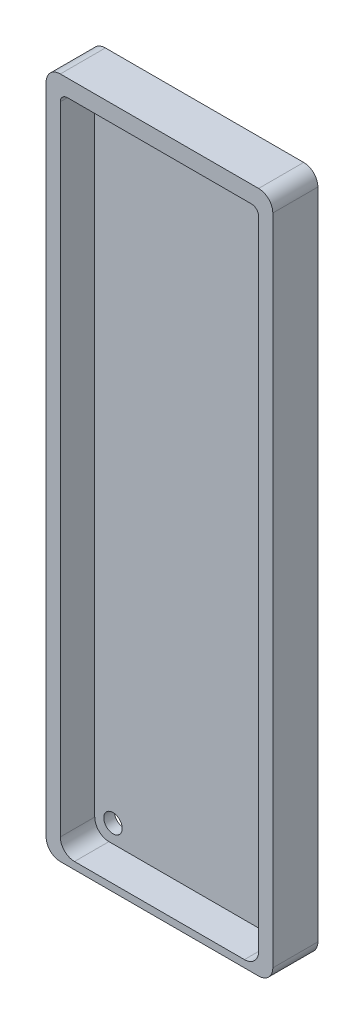
SolidWorks part; units mm, degrees
material "Plastique personnalisé"
ref_plane "Plan de face" through (0, 0, 0) normal (0, 0, 1) x (1, 0, 0)
ref_plane "Plan de dessus" through (0, 0, 0) normal (0, 1, 0) x (1, 0, 0)
ref_plane "Plan de droite" through (0, 0, 0) normal (1, 0, 0) x (0, 0, -1)
sketch "Model" plane through (0, 0, 0) normal (0, 0, 1) x (1, 0, 0)
  line L1773 (110.49, -34.8139) -> (110.49, -38.6239)
  line L1774 (83.82, -33.5439) -> (109.22, -33.5439)
  line L1775 (82.55, -38.6239) -> (82.55, -34.8139)
  line L1776 (82.55, -39.8939) -> (82.55, -123.7139)
  line L1777 (110.49, -39.8939) -> (110.49, -123.7139)
  line L1778 (82.55, -39.8939) -> (82.55, -38.6239)
  line L1779 (110.49, -39.8939) -> (110.49, -38.6239)
  line L1780 (85.09, -126.2539) -> (107.95, -126.2539)
  spline S0 degree 3 poles (109.22, -36.0839) (109.22, -36.5377) (108.9779, -36.9569) (108.585, -37.1838) knots 0 0 0 0 1 1 1 1
  spline S1 degree 3 poles (108.585, -37.1838) (108.1921, -37.4106) (107.7079, -37.4106) (107.315, -37.1838) knots 0 0 0 0 1 1 1 1
  spline S2 degree 3 poles (107.315, -37.1838) (106.9221, -36.9569) (106.68, -36.5377) (106.68, -36.0839) knots 0 0 0 0 1 1 1 1
  spline S3 degree 3 poles (106.68, -36.0839) (106.68, -35.6302) (106.9221, -35.2109) (107.315, -34.9841) knots 0 0 0 0 1 1 1 1
  spline S4 degree 3 poles (107.315, -34.9841) (107.7079, -34.7572) (108.1921, -34.7572) (108.585, -34.9841) knots 0 0 0 0 1 1 1 1
  spline S5 degree 3 poles (108.585, -34.9841) (108.9779, -35.2109) (109.22, -35.6302) (109.22, -36.0839) knots 0 0 0 0 1 1 1 1
  spline S6 degree 3 poles (86.36, -36.0839) (86.36, -36.5377) (86.1179, -36.9569) (85.725, -37.1838) knots 0 0 0 0 1 1 1 1
  spline S7 degree 3 poles (85.725, -37.1838) (85.3321, -37.4106) (84.8479, -37.4106) (84.455, -37.1838) knots 0 0 0 0 1 1 1 1
  spline S8 degree 3 poles (84.455, -37.1838) (84.0621, -36.9569) (83.82, -36.5377) (83.82, -36.0839) knots 0 0 0 0 1 1 1 1
  spline S9 degree 3 poles (83.82, -36.0839) (83.82, -35.6302) (84.0621, -35.2109) (84.455, -34.9841) knots 0 0 0 0 1 1 1 1
  spline S10 degree 3 poles (84.455, -34.9841) (84.8479, -34.7572) (85.3321, -34.7572) (85.725, -34.9841) knots 0 0 0 0 1 1 1 1
  spline S11 degree 3 poles (85.725, -34.9841) (86.1179, -35.2109) (86.36, -35.6302) (86.36, -36.0839) knots 0 0 0 0 1 1 1 1
  spline S12 degree 3 poles (110.49, -34.8139) (110.49, -34.4771) (110.3562, -34.1541) (110.118, -33.9159) knots 0 0 0 0 1 1 1 1
  spline S13 degree 3 poles (110.118, -33.9159) (109.8799, -33.6777) (109.5568, -33.5439) (109.22, -33.5439) knots 0 0 0 0 1 1 1 1
  spline S14 degree 3 poles (83.82, -33.5439) (83.4832, -33.5439) (83.1601, -33.6777) (82.922, -33.9159) knots 0 0 0 0 1 1 1 1
  spline S15 degree 3 poles (82.922, -33.9159) (82.6838, -34.1541) (82.55, -34.4771) (82.55, -34.8139) knots 0 0 0 0 1 1 1 1
  spline S16 degree 3 poles (82.55, -123.7139) (82.55, -124.3876) (82.8176, -125.0336) (83.2939, -125.51) knots 0 0 0 0 1 1 1 1
  spline S17 degree 3 poles (83.2939, -125.51) (83.7703, -125.9863) (84.4163, -126.2539) (85.09, -126.2539) knots 0 0 0 0 1 1 1 1
  spline S18 degree 3 poles (107.95, -126.2539) (108.6236, -126.2539) (109.2697, -125.9863) (109.7461, -125.51) knots 0 0 0 0 1 1 1 1
  spline S19 degree 3 poles (109.7461, -125.51) (110.2224, -125.0336) (110.49, -124.3876) (110.49, -123.7139) knots 0 0 0 0 1 1 1 1
  spline S20 degree 3 poles (86.36, -123.7139) (86.36, -124.1677) (86.1179, -124.5869) (85.725, -124.8138) knots 0 0 0 0 1 1 1 1
  spline S21 degree 3 poles (85.725, -124.8138) (85.3321, -125.0406) (84.8479, -125.0406) (84.455, -124.8138) knots 0 0 0 0 1 1 1 1
  spline S22 degree 3 poles (84.455, -124.8138) (84.0621, -124.5869) (83.82, -124.1677) (83.82, -123.7139) knots 0 0 0 0 1 1 1 1
  spline S23 degree 3 poles (83.82, -123.7139) (83.82, -123.2602) (84.0621, -122.8409) (84.455, -122.6141) knots 0 0 0 0 1 1 1 1
  spline S24 degree 3 poles (84.455, -122.6141) (84.8479, -122.3872) (85.3321, -122.3872) (85.725, -122.6141) knots 0 0 0 0 1 1 1 1
  spline S25 degree 3 poles (85.725, -122.6141) (86.1179, -122.8409) (86.36, -123.2602) (86.36, -123.7139) knots 0 0 0 0 1 1 1 1
  spline S26 degree 3 poles (109.22, -123.7139) (109.22, -124.1677) (108.9779, -124.5869) (108.585, -124.8138) knots 0 0 0 0 1 1 1 1
  spline S27 degree 3 poles (108.585, -124.8138) (108.1921, -125.0406) (107.7079, -125.0406) (107.315, -124.8138) knots 0 0 0 0 1 1 1 1
  spline S28 degree 3 poles (107.315, -124.8138) (106.9221, -124.5869) (106.68, -124.1677) (106.68, -123.7139) knots 0 0 0 0 1 1 1 1
  spline S29 degree 3 poles (106.68, -123.7139) (106.68, -123.2602) (106.9221, -122.8409) (107.315, -122.6141) knots 0 0 0 0 1 1 1 1
  spline S30 degree 3 poles (107.315, -122.6141) (107.7079, -122.3872) (108.1921, -122.3872) (108.585, -122.6141) knots 0 0 0 0 1 1 1 1
  spline S31 degree 3 poles (108.585, -122.6141) (108.9779, -122.8409) (109.22, -123.2602) (109.22, -123.7139) knots 0 0 0 0 1 1 1 1
extrude "Boss.-Extru.1" add sketch "Model" along normal blind 1.5
sketch "Esquisse1" plane through (0, 0, 0) normal (0, 0, -1) x (-1, 0, 0)
  line L0 (-96.52, -33.5439) -> (-115.865, -33.5439) construction
  line L1 (-109.22, -33.5439) -> (-83.82, -33.5439) construction
  line L2 (-110.49, -43.7978) -> (-110.49, -28.2724) construction
  line L3 (-110.49, -123.7139) -> (-110.49, -34.8139) construction
  line L4 (-96.52, -33.5439) -> (-77.5062, -33.5439) construction
  line L5 (-82.55, -44.1721) -> (-82.55, -28.5755) construction
  line L6 (-82.55, -34.8139) -> (-82.55, -123.7139) construction
  line L7 (-96.52, -126.2539) -> (-118.6079, -126.2539) construction
  line L8 (-85.09, -126.2539) -> (-107.95, -126.2539) construction
  line L9 (-118.6079, -126.2539) -> (-70.8635, -126.2539) construction
  line L10 (-110.49, -109.9168) -> (-110.49, -132.8125) construction
  line L11 (-82.55, -108.7873) -> (-82.55, -133.2125) construction
  line L12 (-87.9303, -127.2639) -> (-124.6351, -127.2639) construction
  line L13 (-109.49, -33.5439) -> (-83.55, -33.5439)
  line L14 (-110.49, -34.5439) -> (-110.49, -124.2539)
  line L15 (-108.49, -126.2539) -> (-84.55, -126.2539)
  line L16 (-82.55, -34.5439) -> (-82.55, -124.2539)
  line L17 (-110.49, -127.2639) -> (-82.55, -127.2639) construction
  line L18 (-124.6351, -127.2639) -> (-68.2696, -127.2639) construction
  line L19 (-112.2458, -115.6849) -> (-112.49, -134.0257) construction
  line L20 (-80.55, -113.8817) -> (-80.55, -139.2) construction
  line L21 (-80.55, -125.2639) -> (-80.55, -33.1529) construction
  line L22 (-112.49, -49.0821) -> (-112.49, -27.4348) construction
  line L23 (-112.49, -33.1529) -> (-112.49, -125.2639) construction
  line L24 (-92.2697, -31.1529) -> (-118.4336, -31.1529) construction
  line L25 (-82.55, -31.1529) -> (-110.49, -31.1529) construction
  line L26 (-110.49, -31.1529) -> (-82.55, -31.1529)
  line L28 (-112.49, -33.1529) -> (-112.49, -125.2639)
  line L29 (-110.49, -127.2639) -> (-82.55, -127.2639)
  line L30 (-80.55, -33.1529) -> (-80.55, -125.2639)
  arc A0 (-83.55, -33.5439) -> (-82.55, -34.5439) centre (-83.55, -34.5439) cw
  arc A1 (-109.49, -33.5439) -> (-110.49, -34.5439) centre (-109.49, -34.5439) ccw
  arc A2 (-84.55, -126.2539) -> (-82.55, -124.2539) centre (-84.55, -124.2539) ccw
  arc A3 (-110.49, -124.2539) -> (-108.49, -126.2539) centre (-108.49, -124.2539) ccw
  arc A6 (-82.55, -127.2639) -> (-80.55, -125.2639) centre (-82.55, -125.2639) ccw
  arc A7 (-112.49, -125.2639) -> (-110.49, -127.2639) centre (-110.49, -125.2639) ccw
  arc A8 (-112.49, -33.1529) -> (-110.49, -31.1529) centre (-110.49, -33.1529) cw
  arc A9 (-80.55, -33.1529) -> (-82.55, -31.1529) centre (-82.55, -33.1529) ccw
  point P30 (-110.49, -33.5439)
  point P33 (-82.55, -126.2539)
  point P63 (-112.49, -31.1529)
  point P66 (-80.55, -127.2639)
  dimension "D1" = 1
  dimension "D2" = 2
  dimension "D3" = 2
  dimension "D4" = 2
  dimension "D5" = 2
extrude "Boss.-Extru.2" add sketch "Esquisse1" against normal up to surface (6.35 mm away)
sketch "Esquisse2" plane through (0, 0, 1.5) normal (0, 0, 1) x (1, 0, 0)
  line L0 (82.8629, -122.8035) -> (81.7189, -124.05)
  line L1 (81.8173, -35.4386) -> (83.866, -35.4386)
  line L2 (81.8173, -35.4386) -> (81.8173, -32.7164)
  line L3 (81.8173, -32.7164) -> (83.866, -32.7164)
  line L4 (83.866, -35.4386) -> (83.866, -32.7164)
  line L5 (108.6397, -32.792) -> (111.0237, -32.792)
  line L6 (108.6397, -32.792) -> (108.6397, -34.7862)
  line L7 (108.6397, -34.7862) -> (111.0237, -34.7862)
  line L8 (111.0237, -32.792) -> (111.0237, -34.7862)
  line L9 (81.7189, -124.05) -> (82.8629, -126.4489)
  line L10 (82.8629, -126.4489) -> (85.4924, -126.7819)
  line L11 (85.4924, -126.7819) -> (85.4412, -125.8172)
  line L12 (85.4412, -125.8172) -> (83.7935, -125.0232)
  line L13 (83.7935, -125.0232) -> (83.0593, -123.828)
  line L14 (83.0593, -123.828) -> (82.8629, -122.8035)
  line L15 (111.0798, -122.6986) -> (110.0172, -123.5038)
  line L16 (110.0172, -123.5038) -> (109.2019, -125.1958)
  line L17 (109.2019, -125.1958) -> (107.3198, -125.5565)
  line L18 (107.3198, -125.5565) -> (107.1787, -126.6708)
  line L19 (107.1787, -126.6708) -> (110.2746, -126.6154)
  line L20 (110.2746, -126.6154) -> (111.5063, -125.4688)
  line L21 (111.5063, -125.4688) -> (111.0798, -122.6986)
extrude "Boss.-Extru.3" add sketch "Esquisse2" against normal up to surface (1.5 mm away) up to face at (83.164, -33.9039, 0)
sketch "Esquisse3" plane through (0, 0, 0) normal (0, 0, -1) x (-1, 0, 0)
  line L0 (-107.9524, -36.0805) -> (-78.6596, -36.0805) construction
  line L1 (-107.9524, -36.0805) -> (-107.9524, -128.1578) construction
  line L2 (-107.98, -123.7132) -> (-85.12, -123.5762) construction
  circle A0 centre (-107.9524, -36.0805) radius 1.3
  circle A1 centre (-85.12, -36.0852) radius 1.3
  circle A2 centre (-107.98, -123.7132) radius 1.3
  circle A3 centre (-85.12, -123.7133) radius 1.3
  dimension "D1" = 2.6
  dimension "D2" = 2.6
  dimension "D3" = 2.6
  dimension "D4" = 2.6
extrude "Enlèv. mat.-Extru.1" cut sketch "Esquisse3" against normal through all
